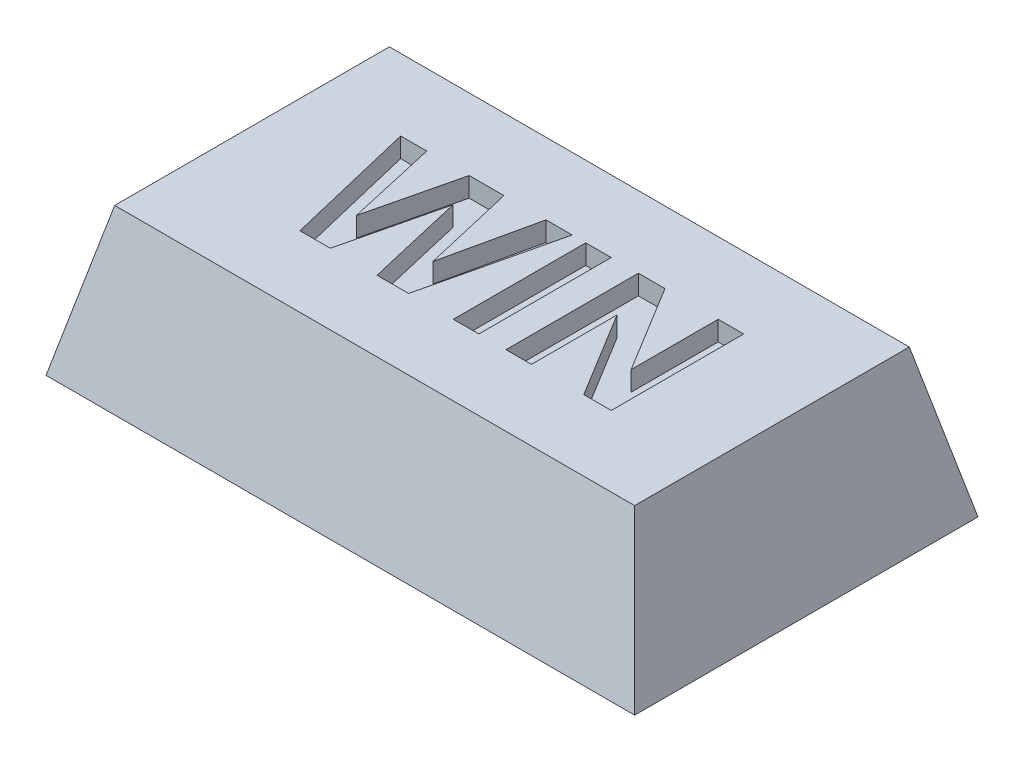
SolidWorks part; units mm, degrees
ref_plane "Front Plane" through (0, 0, 0) normal (0, 0, 1) x (1, 0, 0)
ref_plane "Top Plane" through (0, 0, 0) normal (0, 1, 0) x (1, 0, 0)
ref_plane "Right Plane" through (0, 0, 0) normal (1, 0, 0) x (0, 0, -1)
sketch "Sketch1" plane through (0, 0, 0) normal (0, 1, 0) x (1, 0, 0)
  line L1 (0, 0) -> (12, 0)
  line L2 (0, 0) -> (0, 7)
  line L3 (0, 7) -> (12, 7)
  line L4 (12, 0) -> (12, 7)
  dimension "D1" = 7
  dimension "D2" = 12
extrude "Boss-Extrude1" add sketch "Sketch1" along normal blind 3
sketch "Sketch2" plane through (0, 0, 0) normal (0, 0, 1) x (1, 0, 0)
  line L0 (0, 0) -> (0.7, 3)
  line L1 (0, 3) -> (12, 3) construction
  line L2 (0.7, 3) -> (0, 3)
  line L3 (0, 3) -> (0, 0)
  line L4 (12, 0) -> (11.3, 3)
  line L5 (11.3, 3) -> (12, 3)
  line L6 (12, 3) -> (12, 0)
  dimension "D1" = 0.7
  dimension "D2" = 0.7
extrude "Cut-Extrude1" cut sketch "Sketch2" against normal blind 7
sketch "Sketch3" plane through (0, 0, 0) normal (1, 0, 0) x (0, 0, -1)
  line L0 (0, 0) -> (0.7, 3)
  line L1 (7, 3) -> (0, 3) construction
  line L2 (0.7, 3) -> (0, 3)
  line L3 (0, 3) -> (0, 0)
  line L4 (7, 3) -> (6.3, 3)
  line L5 (6.3, 3) -> (7, 0)
  line L6 (7, 3) -> (7, 0)
  dimension "D1" = 0.7
  dimension "D2" = 0.7
extrude "Cut-Extrude2" cut sketch "Sketch3" along normal through all both and the other way through all
sketch "Sketch4" plane through (0, 0, 0) normal (0, -1, 0) x (1, 0, 0)
  line L0 (6, 0) -> (6, -7) construction
  line L1 (0, 0) -> (12, 0) construction
  line L2 (12, -7) -> (0, -7) construction
  line L3 (0, -3.5) -> (12, -3.5) construction
  line L4 (0, -7) -> (0, 0) construction
  line L5 (12, 0) -> (12, -7) construction
  circle A0 centre (6, -3.5) radius 1.8
  dimension "D1" = 3.6
extrude "Cut-Extrude3" cut sketch "Sketch4" against normal blind 0.8
sketch "Sketch5" plane through (0, 3, 0) normal (0, 1, 0) x (1, 0, 0)
  text T0 "WIN" font "Arial" height 2.7
extrude "Cut-Extrude4" cut sketch "Sketch5" against normal blind 0.4
